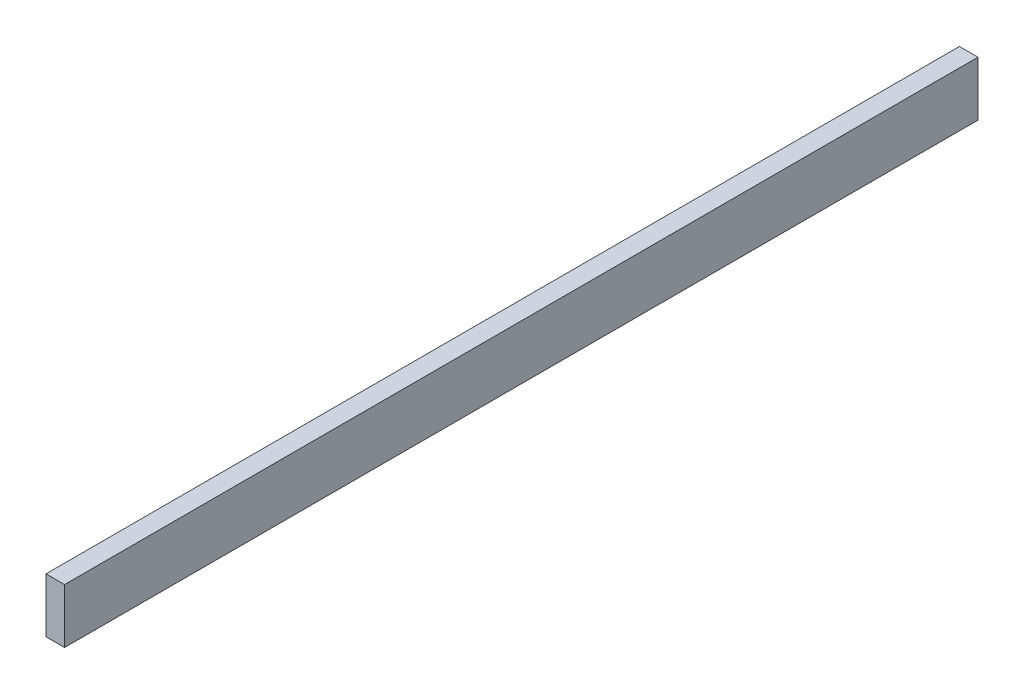
SolidWorks part; units mm, degrees
ref_plane "Front Plane" through (0, 0, 0) normal (0, 0, 1) x (1, 0, 0)
ref_plane "Top Plane" through (0, 0, 0) normal (0, 1, 0) x (1, 0, 0)
ref_plane "Right Plane" through (0, 0, 0) normal (1, 0, 0) x (0, 0, -1)
sketch "Sketch1" plane through (0, 0, 0) normal (0, 0, 1) x (1, 0, 0)
  line L1 (10.16, 29.845) -> (-10.16, 29.845)
  line L2 (10.16, 29.845) -> (10.16, -29.845)
  line L3 (10.16, -29.845) -> (-10.16, -29.845)
  line L4 (-10.16, 29.845) -> (-10.16, -29.845)
  line L5 (10.16, 29.845) -> (-10.16, -29.845) construction
  line L6 (10.16, -29.845) -> (-10.16, 29.845) construction
  point P0 (0, 0)
  dimension "D1" = 20.32
  dimension "D2" = 59.69
extrude "Boss-Extrude1" add sketch "Sketch1" along normal blind 1000
